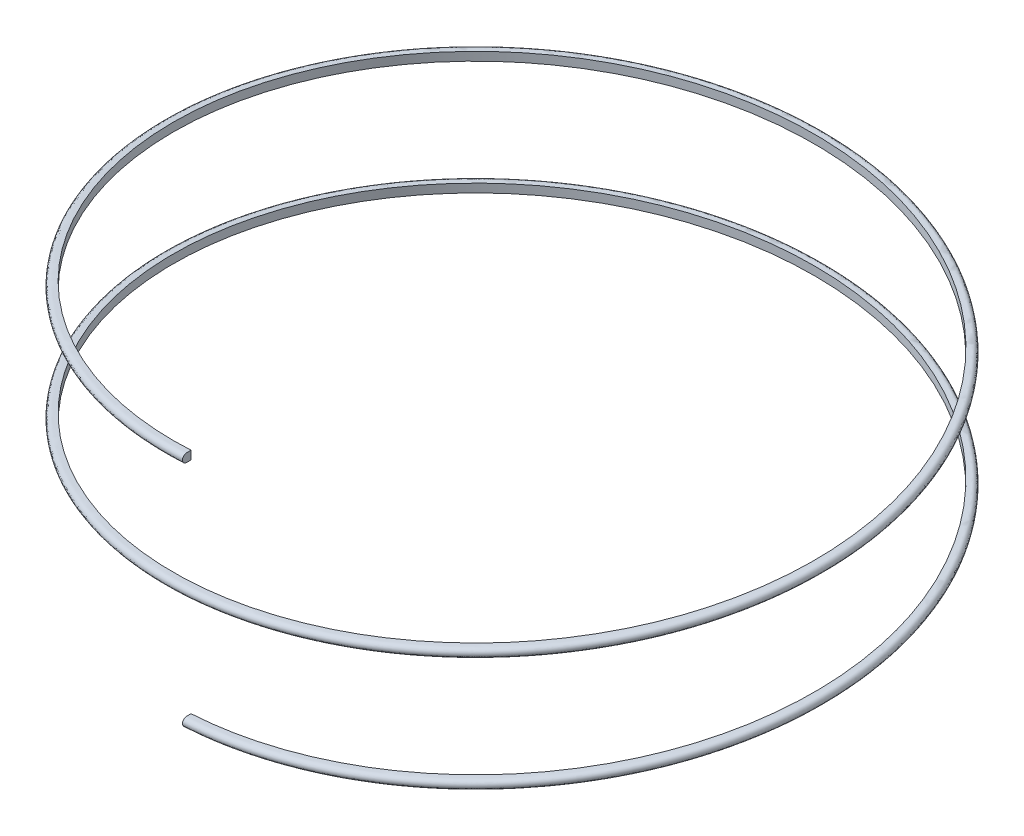
SolidWorks part; units mm, degrees
ref_plane "Front Plane" through (0, 0, 0) normal (0, 0, 1) x (1, 0, 0)
ref_plane "Top Plane" through (0, 0, 0) normal (0, 1, 0) x (1, 0, 0)
ref_plane "Right Plane" through (0, 0, 0) normal (1, 0, 0) x (0, 0, -1)
sketch "Base Circle" plane through (0, 0, 0) normal (0, 1, 0) x (1, 0, 0)
  circle A0 centre (0, 0) radius 37.6559
  dimension "D1" = 75.3119
curve "Thread Helix" pitch 13.387 height 26.774 turns 2
sketch "Thread Sketch" plane through (0, 0, 0) normal (1, 0, 0) x (0, 0, -1)
  line L0 (-37.6559, 0) -> (-37.6559, -1)
  line L1 (-37.6559, 0) -> (-38.1559, 0)
  line L2 (-37.6559, -1) -> (-38.1559, -1)
  arc A0 (-38.1559, -1) -> (-38.1559, 0) centre (-38.1559, -0.5) cw
  dimension "D1" = 1
  dimension "D3" = 0.5
sweep "Thread Sweep" add profiles "Thread Sketch" path "Thread Helix"
